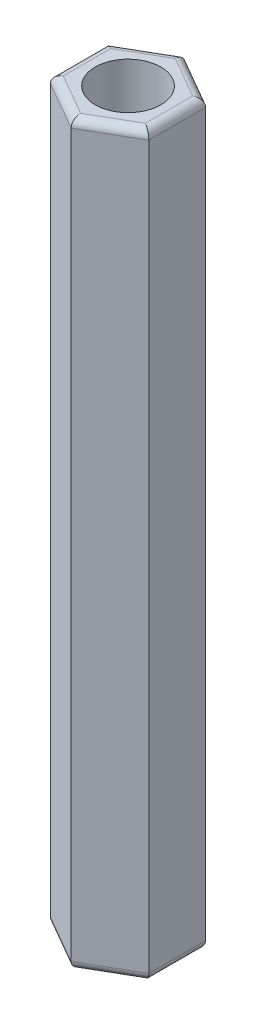
SolidWorks part; units mm, degrees
ref_plane "前视基准面" through (0, 0, 0) normal (0, 0, 1) x (1, 0, 0)
ref_plane "上视基准面" through (0, 0, 0) normal (0, 1, 0) x (1, 0, 0)
ref_plane "右视基准面" through (0, 0, 0) normal (1, 0, 0) x (0, 0, -1)
sketch "草图1" plane through (0, 0, 0) normal (0, 1, 0) x (1, 0, 0)
  line L1 (3, -1.7321) -> (3, 1.7321)
  line L2 (3, 1.7321) -> (0, 3.4641)
  line L3 (0, 3.4641) -> (-3, 1.7321)
  line L4 (-3, 1.7321) -> (-3, -1.7321)
  line L5 (-3, -1.7321) -> (0, -3.4641)
  line L6 (0, -3.4641) -> (3, -1.7321)
  circle A0 centre (0, 0) radius 3 construction
  circle A1 centre (0, 0) radius 2
  dimension "D2" = 4
  dimension "D1" = 6
extrude "凸台-拉伸1" add sketch "草图1" along normal blind 45
fillet "圆角1" radius 0.5 12 edges at (-1.5, 45, 2.5981) (-3, 45, 0) (-1.5, 45, -2.5981) (1.5, 45, -2.5981) (3, 45, 0) (1.5, 45, 2.5981) (-1.5, 0, 2.5981) (1.5, 0, 2.5981) (3, 0, 0) (1.5, 0, -2.5981) (-1.5, 0, -2.5981) (-3, 0, 0)
